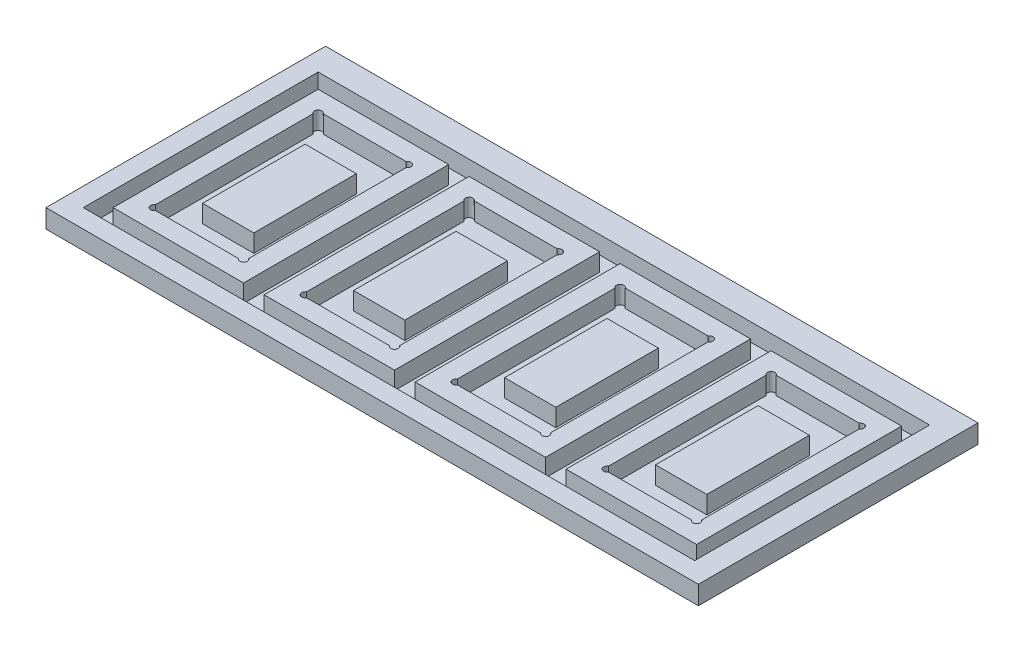
SolidWorks part; units mm, degrees
material "6061 Alloy"
ref_plane "Front Plane" through (0, 0, 0) normal (0, 0, 1) x (1, 0, 0)
ref_plane "Top Plane" through (0, 0, 0) normal (0, 1, 0) x (1, 0, 0)
ref_plane "Right Plane" through (0, 0, 0) normal (1, 0, 0) x (0, 0, -1)
sketch "Sketch1" plane through (0, 0, 0) normal (0, 1, 0) x (1, 0, 0)
  line L1 (-175, -75) -> (175, -75)
  line L2 (-175, -75) -> (-175, 75)
  line L3 (-175, 75) -> (175, 75)
  line L4 (175, -75) -> (175, 75)
  line L5 (-175, -75) -> (175, 75) construction
  line L6 (-175, 75) -> (175, -75) construction
  point P0 (0, 0)
  dimension "D1" = 350
  dimension "D2" = 150
extrude "Boss-Extrude1" add sketch "Sketch1" along normal blind 10
sketch "Sketch2" plane through (0, 10, 0) normal (0, 1, 0) x (1, 0, 0)
  line L0 (98.7562, 43) -> (143.2438, 43)
  line L1 (86, -57) -> (156, -57)
  line L2 (86, -57) -> (86, 53)
  line L3 (86, 53) -> (156, 53)
  line L4 (156, -57) -> (156, 53)
  line L5 (86, -57) -> (156, 53) construction
  line L6 (86, 53) -> (156, -57) construction
  line L7 (146, -44.2438) -> (146, 40.2438)
  line L8 (98.7562, -47) -> (143.2438, -47)
  line L9 (96, -44.2438) -> (96, 40.2438)
  line L10 (96, 43) -> (146, 43) construction
  line L11 (96, -47) -> (96, 43) construction
  line L12 (146, -47) -> (146, 43) construction
  line L13 (96, -47) -> (146, -47) construction
  line L14 (-175, -75) -> (175, -75) construction
  line L15 (108, 24) -> (135.5, 24)
  line L16 (108, 24) -> (108, -31)
  line L17 (108, -31) -> (135.5, -31)
  line L18 (135.5, 24) -> (135.5, -31)
  line L24 (96, -47) -> (96, -44.2438) construction
  line L25 (96, -47) -> (98.7562, -47) construction
  line L26 (143.2438, -47) -> (146, -47) construction
  line L27 (146, -47) -> (146, -44.2438) construction
  line L28 (96, 43) -> (97.0607, 41.9393) construction
  line L29 (146, 43) -> (146, 40.2438) construction
  line L30 (96, 43) -> (98.7562, 43) construction
  line L31 (96, 43) -> (96, 40.2438) construction
  line L32 (146, 43) -> (144.9393, 41.9393) construction
  line L33 (146, -47) -> (144.9393, -45.9393) construction
  line L34 (96, -47) -> (97.0607, -45.9393) construction
  line L35 (5, 53) -> (75, 53)
  line L36 (17.7562, 43) -> (62.2438, 43)
  line L37 (75, -57) -> (75, 53)
  line L38 (65, -44.2438) -> (65, 40.2438)
  line L39 (15, -44.2438) -> (15, 40.2438)
  line L40 (5, -57) -> (5, 53)
  line L41 (5, -57) -> (75, -57)
  line L42 (17.7562, -47) -> (62.2438, -47)
  line L43 (27, 24) -> (27, -31)
  line L44 (27, -31) -> (54.5, -31)
  line L45 (54.5, 24) -> (54.5, -31)
  line L46 (27, 24) -> (54.5, 24)
  line L47 (-76, 53) -> (-6, 53)
  line L48 (-63.2438, 43) -> (-18.7562, 43)
  line L49 (-6, -57) -> (-6, 53)
  line L50 (-16, -44.2438) -> (-16, 40.2438)
  line L51 (-66, -44.2438) -> (-66, 40.2438)
  line L52 (-76, -57) -> (-76, 53)
  line L53 (-76, -57) -> (-6, -57)
  line L54 (-63.2438, -47) -> (-18.7562, -47)
  line L55 (-54, 24) -> (-54, -31)
  line L56 (-54, -31) -> (-26.5, -31)
  line L57 (-26.5, 24) -> (-26.5, -31)
  line L58 (-54, 24) -> (-26.5, 24)
  line L59 (-157, 53) -> (-87, 53)
  line L60 (-144.2438, 43) -> (-99.7562, 43)
  line L61 (-87, -57) -> (-87, 53)
  line L62 (-97, -44.2438) -> (-97, 40.2438)
  line L63 (-147, -44.2438) -> (-147, 40.2438)
  line L64 (-157, -57) -> (-157, 53)
  line L65 (-157, -57) -> (-87, -57)
  line L66 (-144.2438, -47) -> (-99.7562, -47)
  line L67 (-135, 24) -> (-135, -31)
  line L68 (-135, -31) -> (-107.5, -31)
  line L69 (-107.5, 24) -> (-107.5, -31)
  line L70 (-135, 24) -> (-107.5, 24)
  line L73 (-175, 75) -> (-175, -75) construction
  line L79 (-165, 61) -> (163, 61)
  line L80 (-165, 61) -> (-165, -65)
  line L81 (-165, -65) -> (163, -65)
  line L82 (163, 61) -> (163, -65)
  arc A4 (146, 40.2438) -> (143.2438, 43) centre (144.9393, 41.9393) ccw
  arc A5 (98.7562, 43) -> (96, 40.2438) centre (97.0607, 41.9393) ccw
  arc A6 (96, -44.2438) -> (98.7562, -47) centre (97.0607, -45.9393) ccw
  arc A7 (143.2438, -47) -> (146, -44.2438) centre (144.9393, -45.9393) ccw
  arc A8 (65, 40.2438) -> (62.2438, 43) centre (63.9393, 41.9393) ccw
  arc A9 (17.7562, 43) -> (15, 40.2438) centre (16.0607, 41.9393) ccw
  arc A10 (62.2438, -47) -> (65, -44.2438) centre (63.9393, -45.9393) ccw
  arc A11 (15, -44.2438) -> (17.7562, -47) centre (16.0607, -45.9393) ccw
  arc A12 (-16, 40.2438) -> (-18.7562, 43) centre (-17.0607, 41.9393) ccw
  arc A13 (-63.2438, 43) -> (-66, 40.2438) centre (-64.9393, 41.9393) ccw
  arc A14 (-18.7562, -47) -> (-16, -44.2438) centre (-17.0607, -45.9393) ccw
  arc A15 (-66, -44.2438) -> (-63.2438, -47) centre (-64.9393, -45.9393) ccw
  arc A16 (-97, 40.2438) -> (-99.7562, 43) centre (-98.0607, 41.9393) ccw
  arc A17 (-144.2438, 43) -> (-147, 40.2438) centre (-145.9393, 41.9393) ccw
  arc A18 (-99.7562, -47) -> (-97, -44.2438) centre (-98.0607, -45.9393) ccw
  arc A19 (-147, -44.2438) -> (-144.2438, -47) centre (-145.9393, -45.9393) ccw
  dimension "D3" = 4
  dimension "D13" = 45
  dimension "D17" = 4
  dimension "D22" = 4
  dimension "D23" = 4
  dimension "D1" = 110
  dimension "D4" = 55
  dimension "D5" = 27.5
  dimension "D6" = 8
  dimension "D7" = 12
  dimension "D8" = 7
  dimension "D9" = 19
  dimension "D10" = 70
  dimension "D11" = 16
  dimension "D12" = 10.5
  dimension "D14" = 1.5
  dimension "D15" = 45
  dimension "D16" = 1.5
  dimension "D18" = 1.5
  dimension "D19" = 45
  dimension "D20" = 1.5
  dimension "D21" = 45
  dimension "D25" = 11
  dimension "D26" = 10
  dimension "D27" = 8
  dimension "D28" = 8
  dimension "D29" = 10
  dimension "D2" = 10
  dimension "D24" = 4
extrude "Cut-Extrude1" cut sketch "Sketch2" against normal blind 9.5 contours L82 L79 L80 L81 L65 L64 L59 L61 L53 L52 L47 L49 L41 L40 L35 L37 L4 L1 L2 L3 | L63 A19 L66 A18 L62 A16 L60 A17 L67 L70 L69 L68 | L51 A15 L54 A14 L50 A12 L48 A13 L55 L58 L57 L56 | L39 A11 L42 A10 L38 A8 L36 A9 L43 L46 L45 L44 | L8 A7 L7 A4 L0 A5 L9 A6 L15 L18 L17 L16
